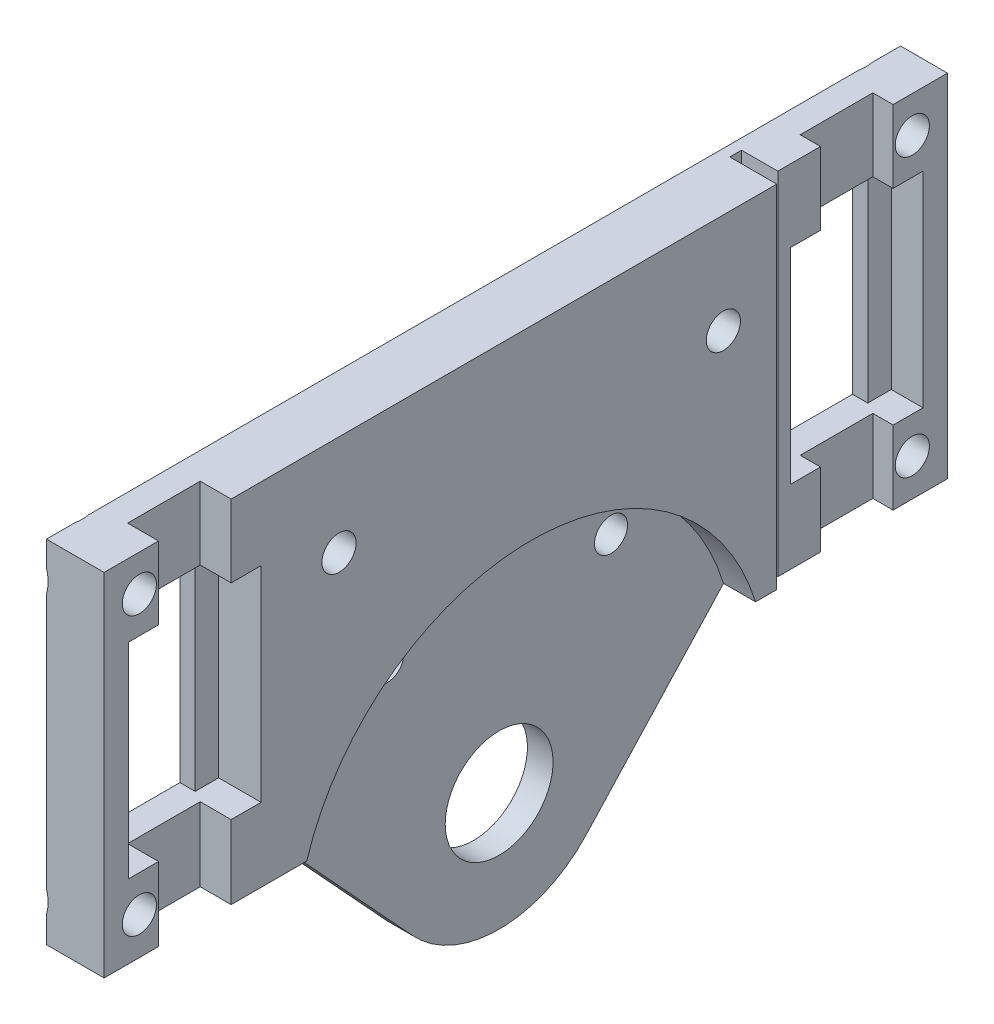
SolidWorks part; units mm, degrees
ref_plane "Face" through (0, 0, 0) normal (0, 0, 1) x (1, 0, 0)
ref_plane "Dessus" through (0, 0, 0) normal (0, 1, 0) x (1, 0, 0)
ref_plane "Droite" through (0, 0, 0) normal (1, 0, 0) x (0, 0, -1)
sketch "Esquisse2" plane through (0, 0, 0) normal (1, 0, 0) x (0, 0, -1)
  line L0 (-40, -15) -> (40, -15)
  line L4 (-40, -15) -> (-40, 70)
  line L8 (-40, 70) -> (40, 70)
  line L9 (40, 70) -> (40, -15)
  dimension "D1" = 70
  dimension "D2" = 15
  dimension "D3" = 40
  dimension "D4" = 40
extrude "plaque" add sketch "Esquisse2" along normal blind 5.4
ref_plane "Plan_posic" through (2.4, 0, 0) normal (-1, 0, 0) x (0, 0, 1)
sketch "Esquisse13" plane through (0, 0, 0) normal (1, 0, 0) x (0, 0, -1)
  line L0 (-7, 20) -> (-7, 0)
  line L1 (-7, 20) -> (7, 20)
  line L2 (-7, 0) -> (7, 0)
  line L3 (7, 20) -> (7, 0)
  line L4 (-7, 20) -> (7, 0) construction
  line L5 (-7, 0) -> (7, 20) construction
  line L6 (0, 10) -> (0, 0) construction
  line L7 (0, 0) -> (0, -16.5568) construction
  point P1 (0, 10)
  dimension "D1" = 20
  dimension "D2" = 14
  dimension "D3" = 180
  dimension "D4" = 20
extrude "extension plaque pour posic" [suppressed] add sketch "Esquisse13" along normal up to surface (5.8 mm away)
sketch "Esquisse14" plane through (0, 0, 0) normal (1, 0, 0) x (0, 0, -1)
  circle A0 centre (0, -12) radius 5.05
  dimension "D1" = 10.1
  dimension "D2" = 12
sketch "Esquisse15" plane through (2.4, 0, 0) normal (-1, 0, 0) x (0, 0, 1)
  circle A0 centre (0, -12) radius 22
  dimension "D1" = 12
  dimension "D2" = 44
extrude "dégagement roue" cut sketch "Esquisse15" against normal through all
sketch "Esquisse18" plane through (0, 0, 0) normal (1, 0, 0) x (0, 0, -1)
  line L0 (-5.7851, -6.8944) -> (-7.4469, -5.5) construction
  line L1 (-7.4469, -5.5) -> (-40, -5.5)
  line L2 (-40, -5.5) -> (-40, -15)
  line L3 (-7.4469, -5.5) -> (7.4469, -5.5)
  line L4 (0, -5.5) -> (0, 0) construction
  line L5 (5.7851, -6.8944) -> (7.4469, -5.5) construction
  line L6 (7.4469, -5.5) -> (40, -5.5)
  line L7 (40, -5.5) -> (40, -15)
  line L8 (40, -15) -> (-40, -15)
  arc A0 (5.7851, -6.8944) -> (-5.7851, -6.8944) centre (0, 0) cw construction
  dimension "D1" = 5.5
  dimension "D2" = 9
  dimension "D3" = 50
extrude "découpe_inférieure" cut sketch "Esquisse18" along normal through all
extrude "renfort_roulement" add sketch "Esquisse14" along normal up to surface (2.4 mm away) thin
sketch "Esquisse20" plane through (0, 0, 0) normal (1, 0, 0) x (0, 0, -1)
  line L0 (-40, 70) -> (40, 70)
  line L1 (40, 70) -> (40, 62.5)
  line L2 (40, 62.5) -> (26, 62.5)
  line L3 (21.1704, 58.7941) -> (15.5592, 37.853)
  line L4 (13.1444, 36) -> (-13.1444, 36)
  line L5 (-15.5592, 37.853) -> (-21.1704, 58.7941)
  line L6 (-26, 62.5) -> (-40, 62.5)
  line L7 (-40, 62.5) -> (-40, 70)
  line L8 (0, 0) -> (0, 36) construction
  line L9 (0, 70) -> (0, 36) construction
  arc A0 (26, 62.5) -> (21.1704, 58.7941) centre (26, 57.5) ccw
  arc A1 (15.5592, 37.853) -> (13.1444, 36) centre (13.1444, 38.5) cw
  arc A2 (-13.1444, 36) -> (-15.5592, 37.853) centre (-13.1444, 38.5) cw
  arc A3 (-21.1704, 58.7941) -> (-26, 62.5) centre (-26, 57.5) ccw
  dimension "D1" = 7.5
  dimension "D3" = 2.5
  dimension "D4" = 5
  dimension "D2" = 36
  dimension "D5" = 15
  dimension "D6" = 26
extrude "découpe_supérieure" cut sketch "Esquisse20" along normal through all
sketch "Esquisse26" plane through (0, 0, 0) normal (0, 1, 0) x (1, 0, 0)
  line L0 (5.9, 31.5) -> (5.9, -31.5) construction
  line L1 (0, 0) -> (5.9, 0) construction
  line L3 (2.5, 28.1) -> (9.3, 28.1)
  line L4 (2.5, 28.1) -> (2.5, 34.9)
  line L5 (2.5, 34.9) -> (9.3, 34.9)
  line L6 (9.3, 28.1) -> (9.3, 34.9)
  line L7 (2.5, 28.1) -> (9.3, 34.9) construction
  line L8 (2.5, 34.9) -> (9.3, 28.1) construction
  line L9 (2.5, -34.9) -> (9.3, -34.9)
  line L10 (2.5, -34.9) -> (2.5, -28.1)
  line L11 (2.5, -28.1) -> (9.3, -28.1)
  line L12 (9.3, -34.9) -> (9.3, -28.1)
  line L13 (2.5, -34.9) -> (9.3, -28.1) construction
  line L14 (2.5, -28.1) -> (9.3, -34.9) construction
  dimension "D1" = 5.9
  dimension "D2" = 63
  dimension "D3" = 6.8
extrude "dégagement axe 6" cut sketch "Esquisse26" against normal through all and the other way through all
sketch "Esquisse28" plane through (0, 0, 0) normal (0, 1, 0) x (1, 0, 0)
  line L1 (0, 35.5) -> (1.4279, 35.5)
  line L2 (0, 35.5) -> (0, 27.5)
  line L3 (0, 27.5) -> (1.4279, 27.5)
  line L4 (1.4279, 35.5) -> (1.4279, 27.5) construction
  line L5 (5.9, 31.5) -> (1.4279, 31.5) construction
  line L6 (1.4279, 35.5) -> (1.4279, 37.7)
  line L7 (10.3721, 25.3) -> (1.4279, 25.3)
  line L8 (10.3721, 25.3) -> (10.3721, 37.7)
  line L9 (10.3721, 37.7) -> (1.4279, 37.7)
  line L10 (1.4279, 25.3) -> (1.4279, 27.5)
  line L11 (10.3721, 25.3) -> (1.4279, 37.7) construction
  line L12 (10.3721, 37.7) -> (1.4279, 25.3) construction
  line L13 (0, 40) -> (0, 8.936) construction
  line L14 (10.3721, -25.3) -> (1.4279, -25.3)
  line L15 (10.3721, -25.3) -> (10.3721, -37.7)
  line L16 (10.3721, -37.7) -> (1.4279, -37.7)
  line L17 (1.4279, -25.3) -> (1.4279, -27.5)
  line L18 (10.3721, -25.3) -> (1.4279, -37.7) construction
  line L19 (10.3721, -37.7) -> (1.4279, -25.3) construction
  line L20 (1.4279, -31.5) -> (5.9, -31.5) construction
  line L21 (0, -27.5) -> (1.4279, -27.5)
  line L22 (0, -27.5) -> (0, -35.5)
  line L23 (0, -35.5) -> (1.4279, -35.5)
  line L24 (1.4279, -27.5) -> (1.4279, -35.5) construction
  line L25 (1.4279, -35.5) -> (1.4279, -37.7)
  circle A0 centre (5.9, 31.5) radius 6 construction
  circle A1 centre (5.9, -31.5) radius 6 construction
  dimension "D1" = 12
  dimension "D2" = 8
  dimension "D3" = 6.2
extrude "dégagement douille" cut sketch "Esquisse28" along normal blind 19.2 from offset 1.4
sketch "Esquisse29" plane through (5.4, 0, 0) normal (1, 0, 0) x (0, 0, -1)
  line L0 (26.0071, 19.8929) -> (25.2293, 20.6707) construction
  line L1 (36.2858, 20.6) -> (37.7, 19.1858) construction
  line L2 (26.7142, 20.6) -> (25.3, 19.1858) construction
  line L3 (28.1, 20.6) -> (25.3, 20.6) construction
  line L4 (25.3, 1.4) -> (25.3, 20.6) construction
  line L5 (37.7, 20.6) -> (35.5, 20.6) construction
  line L6 (26.7142, 20.6) -> (36.2858, 20.6)
  line L7 (37.7, 20.6) -> (37.7, 1.4) construction
  line L8 (36.9929, 19.8929) -> (37.7707, 20.6707) construction
  line L9 (26.9294, 18.6) -> (36.0706, 18.6)
  arc A0 (25.3, 19.1858) -> (26.7142, 20.6) centre (25.9396, 19.9604) cw
  arc A1 (36.2858, 20.6) -> (37.7, 19.1858) centre (37.0604, 19.9604) cw
  arc A2 (25.3, 19.1858) -> (26.9294, 18.6) centre (26.9294, 21.1591) ccw
  arc A3 (36.0706, 18.6) -> (37.7, 19.1858) centre (36.0706, 21.1591) ccw
  dimension "D1" = 45
  dimension "D3" = 1.1
  dimension "D4" = 2
  dimension "D2" = 2
extrude "degagement angle" [suppressed] cut sketch "Esquisse29" against normal through all
ref_plane "Plan1" through (0, 11, 0) normal (0, 1, 0) x (1, 0, 0)
mirror "Symétrie2" [suppressed] about plane through (0, 11, 0) normal (0, 1, 0)
mirror "Symétrie3" [suppressed] about plane through (0, 0, 0) normal (0, 0, 1)
pattern_linear "Répétition linéaire1" count 2 spacing 26 along (0, 1, 0) of "dégagement douille", "degagement angle", "Symétrie2", "Symétrie3"
sketch "Esquisse19" plane through (0, 0, 0) normal (0, 1, 0) x (1, 0, 0)
  line L0 (5.4, 40) -> (4.4, 40)
  line L1 (4.4, 40) -> (4.4, 24.1)
  line L2 (4.4, 24.1) -> (1, 24.1)
  line L3 (1, 24.1) -> (1, 23)
  line L4 (1, 23) -> (5.4, 23)
  line L5 (5.4, 23) -> (5.4, 40)
  dimension "D1" = 23
  dimension "D2" = 1.1
  dimension "D3" = 1
  dimension "D4" = 1
extrude "Mors_déformable_douille" cut sketch "Esquisse19" against normal through all and the other way through all
sketch "position perçage" plane through (0, 0, 0) normal (1, 0, 0) x (0, 0, -1)
  line L0 (-18, 18) -> (18, 18) construction
  line L1 (0, 18) -> (0, 0) construction
  line L2 (-36.7, 24) -> (-36.7, -2) construction
  line L3 (36.7, 24) -> (-36.7, 24) construction
  line L4 (36.7, -2) -> (36.7, 24) construction
  line L5 (0, 18) -> (0, 24) construction
  line L6 (0, 24) -> (0, 34) construction
  line L7 (-34.9, -5.5) -> (-40, -5.5) construction
  line L9 (-40, 62.5) -> (-40, -5.5) construction
  line L10 (-21, 34) -> (21, 34) construction
  dimension "D1" = 36
  dimension "D2" = 18
  dimension "D3" = 3.3
  dimension "D4" = 3.5
  dimension "D5" = 26
  dimension "D6" = 42
  dimension "D7" = 10
hole_wizard "Fraisage pour vis à tête fraisée bombée fendue M31" positions "Esquisse23" profile "Esquisse22" countersink size "M3" standard "Ansi Metric" end condition through all
sketch "Esquisse23" plane through (0, 0, 0) normal (-1, 0, 0) x (0, 0, 1)
  point P0 (18, 18)
  point P4 (36.7, 24)
  point P7 (36.7, -2)
  point P10 (21, 34)
sketch "Esquisse22" plane through (0, 18, 18) normal (0, 1, 0) x (0, 0, 1)
  line L0 (0, 0) -> (0, 5.4)
  line L1 (0, 5.4) -> (1.6, 5.4)
  line L2 (1.6, 5.4) -> (1.6, 1.86)
  line L3 (1.6, 1.86) -> (3.46, 0)
  line L5 (3.46, 0) -> (0, 0)
  line L6 (-1.6, 1.86) -> (-3.46, 0) construction
  line L11 (0, -6.35) -> (0, 107.95) construction
  dimension "Diamètre du perçage jusqu'au prochain" = 3.2
  dimension "Profondeur du perçage jusqu'au prochain" = 5.4
  dimension "Diamètre du fraisage entrant" = 6.92
  dimension "Angle du fraisage entrant" = 90
sketch "Esquisse31" plane through (5.4, 0, 0) normal (1, 0, 0) x (0, 0, -1)
  line L0 (40, -5.5) -> (40, 62.5) construction
  line L1 (-40, 62.5) -> (40, 62.5)
  line L2 (-40, 62.5) -> (-40, 27.4)
  line L3 (-40, 27.4) -> (40, 27.4)
  line L4 (40, 62.5) -> (40, 27.4)
  line L5 (37.7, 27.4) -> (34.9, 27.4) construction
extrude "Enlèv. mat.-Extru.1" cut sketch "Esquisse31" against normal up to surface (5.4 mm away) up to face at (0, 18, 21.46)
sketch "Esquisse33" plane through (2.4, 0, 0) normal (1, 0, 0) x (0, 0, -1)
  line L0 (-8.1254, -19.4887) -> (-21.0178, -5.5)
  line L1 (0, 0) -> (0, -12) construction
  line L2 (-21.0178, -5.5) -> (-8.936, -5.5)
  line L3 (-8.936, -5.5) -> (-8.1254, -19.4887)
  line L4 (8.1254, -19.4887) -> (21.0178, -5.5)
  line L5 (8.1254, -19.4887) -> (8.936, -5.5)
  line L6 (8.936, -5.5) -> (21.0178, -5.5)
  arc A1 (-8.936, -5.5) -> (8.936, -5.5) centre (0, -12) ccw construction
extrude "Boss.-Extru.1" add sketch "Esquisse33" against normal up to surface (2.4 mm away) up to face at (0, 26.7358, 39.2226)
mirror "Symétrie4" about plane through (0, 0, 0) normal (0, 0, 1) of "Fraisage pour vis à tête fraisée bombée fendue M31"
sketch "Esquisse34" plane through (2.4, 0, 0) normal (1, 0, 0) x (0, 0, -1)
  line L0 (-10.48, 3.75) -> (10.48, 3.75) construction
  circle A0 centre (-10.48, 3.75) radius 1.55
  circle A1 centre (10.48, 3.75) radius 1.55
  point P4 (0, 3.75)
  point P5 (0, -12)
  dimension "D1" = 3.1
  dimension "D2" = 3.1
  dimension "D3" = 20.96
  dimension "D4" = 15.75
extrude "Enlèv. mat.-Extru.2" cut sketch "Esquisse34" against normal blind 10
